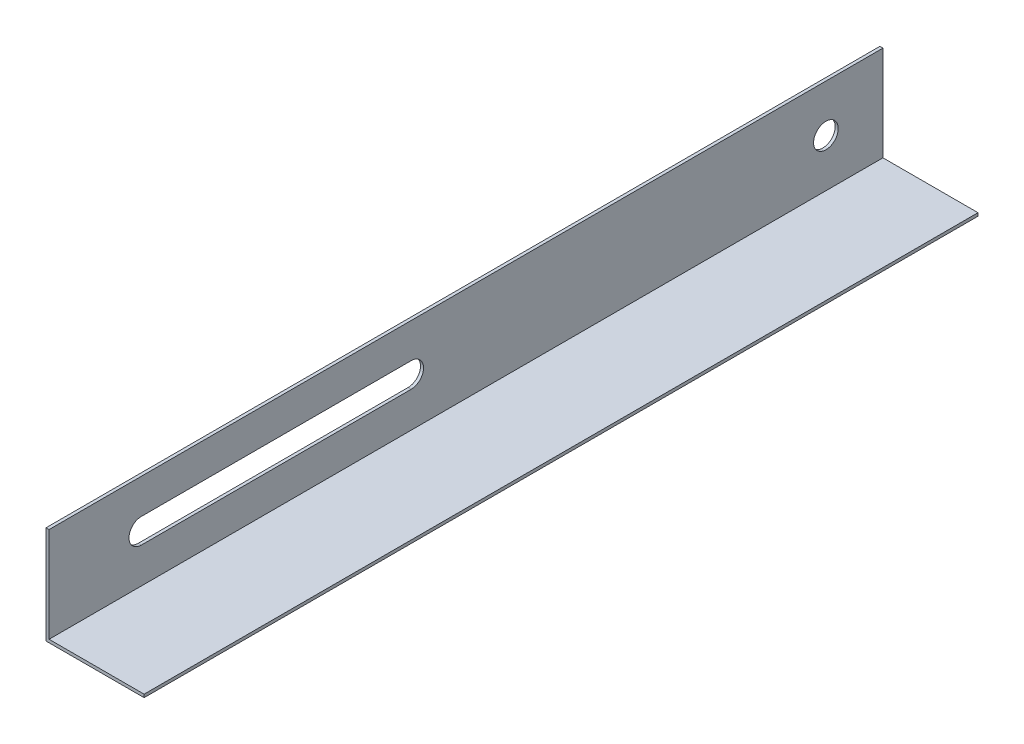
SolidWorks part; units mm, degrees
ref_plane "Front Plane" through (0, 0, 0) normal (0, 0, 1) x (1, 0, 0)
ref_plane "Top Plane" through (0, 0, 0) normal (0, 1, 0) x (1, 0, 0)
ref_plane "Right Plane" through (0, 0, 0) normal (1, 0, 0) x (0, 0, -1)
sketch "Sketch3" plane through (0, 0, 0) normal (0, 0, 1) x (1, 0, 0)
  line L0 (0, 0) -> (0, 49.2125)
  line L1 (0, 49.2125) -> (-1.5875, 49.2125)
  line L2 (-1.5875, 49.2125) -> (-1.5875, -1.5875)
  line L3 (-1.5875, -1.5875) -> (49.2125, -1.5875)
  line L4 (49.2125, -1.5875) -> (49.2125, 0)
  line L5 (49.2125, 0) -> (0, 0)
  dimension "D1" = 1.5875
  dimension "D2" = 1.5875
  dimension "D3" = 50.8
  dimension "D4" = 50.8
extrude "Boss-Extrude2" add sketch "Sketch3" along normal blind 431.8
sketch "Sketch6" plane through (0, 0, 0) normal (1, 0, 0) x (0, 0, -1)
  line L0 (-384.0055, 24.7736) -> (-244.3055, 24.7736) construction
  line L1 (-384.0055, 31.1871) -> (-244.3055, 31.1871)
  line L2 (-384.0055, 18.3601) -> (-244.3055, 18.3601)
  line L3 (-431.8, 0) -> (-431.8, 49.2125) construction
  arc A0 (-384.0055, 31.1871) -> (-384.0055, 18.3601) centre (-384.0055, 24.7736) ccw
  arc A1 (-244.3055, 18.3601) -> (-244.3055, 31.1871) centre (-244.3055, 24.7736) ccw
  point P2 (-314.1555, 24.7736)
  dimension "D1" = 12.827
  dimension "D2" = 139.7
  dimension "D3" = 47.7945
extrude "Cut-Extrude3" cut sketch "Sketch6" against normal blind 127
sketch "Sketch7" plane through (0, 0, 0) normal (1, 0, 0) x (0, 0, -1)
  circle A0 centre (-29.5388, 24.7736) radius 6.3881
  dimension "D1" = 12.7762
extrude "Cut-Extrude4" cut sketch "Sketch7" against normal blind 127
